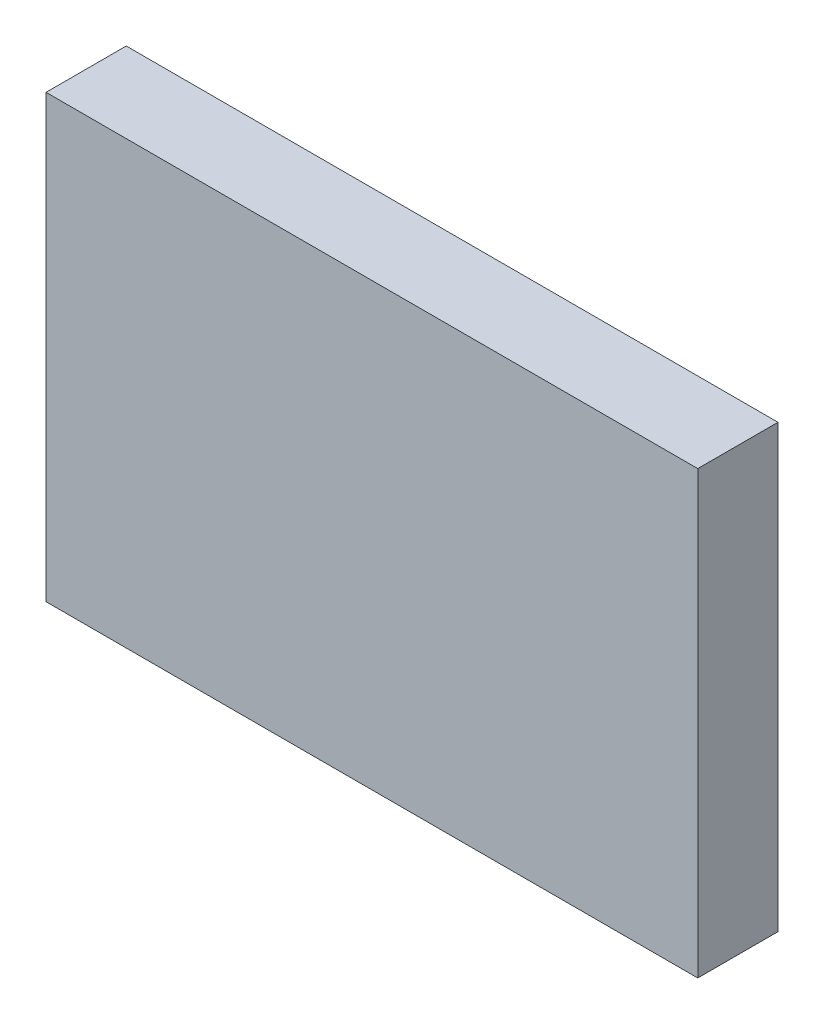
SolidWorks part; units mm, degrees
ref_plane "Front Plane" through (0, 0, 0) normal (0, 0, 1) x (1, 0, 0)
ref_plane "Top Plane" through (0, 0, 0) normal (0, 1, 0) x (1, 0, 0)
ref_plane "Right Plane" through (0, 0, 0) normal (1, 0, 0) x (0, 0, -1)
sketch "Sketch1" plane through (0, 0, 0) normal (0, 0, 1) x (1, 0, 0)
  line L1 (0, 0) -> (65, 0)
  line L2 (0, 0) -> (0, 44)
  line L3 (0, 44) -> (65, 44)
  line L4 (65, 0) -> (65, 44)
  dimension "D1" = 65
  dimension "D2" = 44
extrude "Boss-Extrude1" add sketch "Sketch1" along normal blind 8
